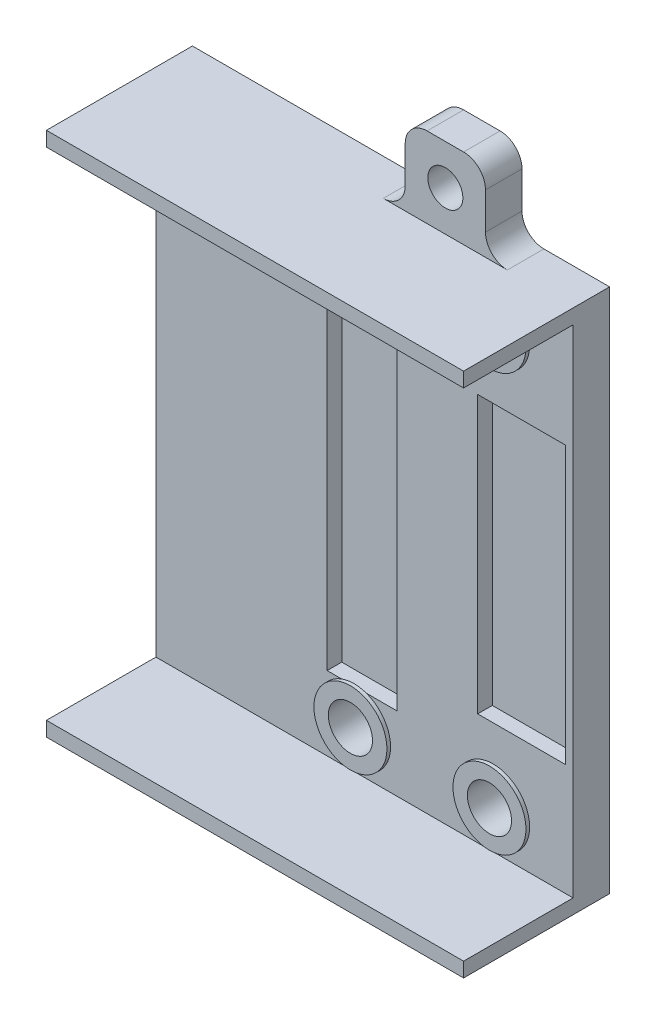
SolidWorks part; units mm, degrees
ref_plane "Front Plane" through (0, 0, 0) normal (0, 0, 1) x (1, 0, 0)
ref_plane "Top Plane" through (0, 0, 0) normal (0, 1, 0) x (1, 0, 0)
ref_plane "Right Plane" through (0, 0, 0) normal (1, 0, 0) x (0, 0, -1)
sketch "Sketch3" plane through (0, 0, 0) normal (0, 0, 1) x (1, 0, 0)
  line L1 (-28.575, 36) -> (28.575, 36)
  line L2 (-28.575, 36) -> (-28.575, -36)
  line L3 (-28.575, -36) -> (28.575, -36)
  line L4 (28.575, 36) -> (28.575, -36)
  line L5 (-28.575, 36) -> (28.575, -36) construction
  line L6 (-28.575, -36) -> (28.575, 36) construction
  point P0 (0, 0)
  dimension "D1" = 72
  dimension "D2" = 57.15
extrude "Boss-Extrude1" add sketch "Sketch3" along normal blind 5
sketch "Sketch5" plane through (0, 0, 5) normal (0, 0, 1) x (1, 0, 0)
  line L12 (28.575, -36) -> (28.575, 36)
  line L13 (28.575, 36) -> (-28.575, 36)
  line L14 (-28.575, 36) -> (-28.575, -36)
  line L15 (-28.575, -36) -> (28.575, -36)
  line L16 (28.575, -36) -> (28.575, 36) construction
  line L17 (28.575, 36) -> (-28.575, 36) construction
  line L18 (-28.575, 36) -> (-28.575, -36) construction
  line L19 (-28.575, -36) -> (28.575, -36) construction
  circle A0 centre (17.621, 28.575) radius 2.1 construction
  circle A21 centre (-1.429, -28.575) radius 2.1 construction
  circle A22 centre (17.621, -28.575) radius 2.1 construction
  circle A23 centre (17.621, 28.575) radius 2.1 construction
  circle A24 centre (17.621, 28.575) radius 3.025
  circle A25 centre (17.621, -28.575) radius 3.025
  circle A26 centre (-1.429, -28.575) radius 3.025
  circle A27 centre (-1.429, 28.575) radius 3.025
  circle A28 centre (17.621, 28.575) radius 5
  circle A29 centre (17.621, -28.575) radius 5
  circle A30 centre (-1.429, -28.575) radius 5
  circle A31 centre (-1.429, 28.575) radius 5
  dimension "D2" = 6.05
  dimension "D3" = 10
  dimension "D1" = 0
extrude "Boss-Extrude2" add sketch "Sketch5" along normal blind 0.5
sketch "Sketch6" plane through (0, 0, 5) normal (0, 0, 1) x (1, 0, 0)
  circle A0 centre (-1.429, 28.575) radius 3.025 construction
  circle A1 centre (17.621, 28.575) radius 3.025 construction
  circle A2 centre (-1.429, -28.575) radius 3.025 construction
  circle A3 centre (17.621, -28.575) radius 3.025 construction
  circle A4 centre (-1.429, 28.575) radius 3.025
  circle A5 centre (17.621, 28.575) radius 3.025
  circle A6 centre (-1.429, -28.575) radius 3.025
  circle A7 centre (17.621, -28.575) radius 3.025
extrude "Cut-Extrude1" cut sketch "Sketch6" against normal blind 4.5
sketch "Sketch8" plane through (0, 0, 5) normal (0, 0, 1) x (1, 0, 0)
  line L1 (-5.115, 23.528) -> (4.485, 23.528)
  line L2 (-5.115, 23.528) -> (-5.115, -23.872)
  line L3 (-5.115, -23.872) -> (4.485, -23.872)
  line L4 (4.485, 23.528) -> (4.485, -23.872)
  line L10 (20.208, -18.696) -> (15.508, -18.696) construction
  line L11 (15.508, 19.204) -> (27.508, 19.204)
  line L13 (15.508, -18.696) -> (27.508, -18.696)
  line L14 (27.508, 19.204) -> (27.508, -18.696)
  line L15 (15.508, -18.696) -> (15.508, -17.796) construction
  line L16 (15.508, 19.204) -> (15.508, -18.696)
  dimension "D1" = 12
extrude "Cut-Extrude2" cut sketch "Sketch8" against normal blind 2
sketch "Sketch10" plane through (0, 0, 5) normal (0, 0, 1) x (1, 0, 0)
  line L0 (28.575, -36) -> (28.575, 36) construction
  line L1 (-28.575, 36) -> (28.575, 36)
  line L2 (-28.575, 36) -> (-28.575, 34)
  line L3 (-28.575, 34) -> (28.575, 34)
  line L4 (28.575, 36) -> (28.575, 34)
  line L6 (-28.575, -36) -> (28.575, -36)
  line L7 (-28.575, -36) -> (-28.575, -34)
  line L8 (-28.575, -34) -> (28.575, -34)
  line L9 (28.575, -36) -> (28.575, -34)
  dimension "D1" = 2
extrude "Boss-Extrude3" add sketch "Sketch10" along normal blind 15
sketch "Sketch11" plane through (0, 0, 0) normal (0, 0, -1) x (-1, 0, 0)
  line L0 (-28.575, 36) -> (28.575, 36) construction
  line L1 (-16.575, 36) -> (-5.575, 36)
  line L2 (-16.575, 36) -> (-16.575, 47)
  line L3 (-16.575, 47) -> (-5.575, 47)
  line L4 (-5.575, 36) -> (-5.575, 47)
  line L5 (-11.075, 36) -> (-11.075, 47)
  line L6 (-28.575, 34) -> (-28.575, 36) construction
  circle A0 centre (-11.075, 41.5) radius 2 construction
  line M7 (28.575, 36) -> (-28.575, 36)
  dimension "D1" = 4
  dimension "D2" = 11
  dimension "D3" = 11
  dimension "D4" = 12
extrude "Boss-Extrude4" add sketch "Sketch11" against normal blind 5 contours L1 L5 L3 L2 | L5 L4 L3 M7
hole_wizard "M4 Clearance Hole1" positions "Sketch14" profile "Sketch13" hole size "M4" standard "ANSI Metric" end condition through all
sketch "Sketch14" plane through (0, 0, 5) normal (0, 0, 1) x (1, 0, 0)
  point P0 (11.075, 41.5)
sketch "Sketch13" plane through (11.075, 41.5, 5) normal (1, 0, 0) x (0, -1, 0)
  line L0 (0, 0) -> (0, 5)
  line L1 (0, 5) -> (2.4, 5)
  line L2 (2.4, 5) -> (2.4, 0)
  line L5 (2.4, 0) -> (0, 0)
  line L11 (0, -6.35) -> (0, 107.95) construction
  dimension "Thru Hole Dia." = 4.8
  dimension "Thru Hole Depth" = 5
mirror "Mirror1" about plane through (0, 0, 0) normal (0, 1, 0) of "Boss-Extrude4", "M4 Clearance Hole1"
fillet "Fillet2" radius 3 8 edges at (5.575, -36, 2.5) (5.575, -47, 2.5) (16.575, -47, 2.5) (16.575, -36, 2.5) (16.575, 47, 2.5) (16.575, 36, 2.5) (5.575, 47, 2.5) (5.575, 36, 2.5)
